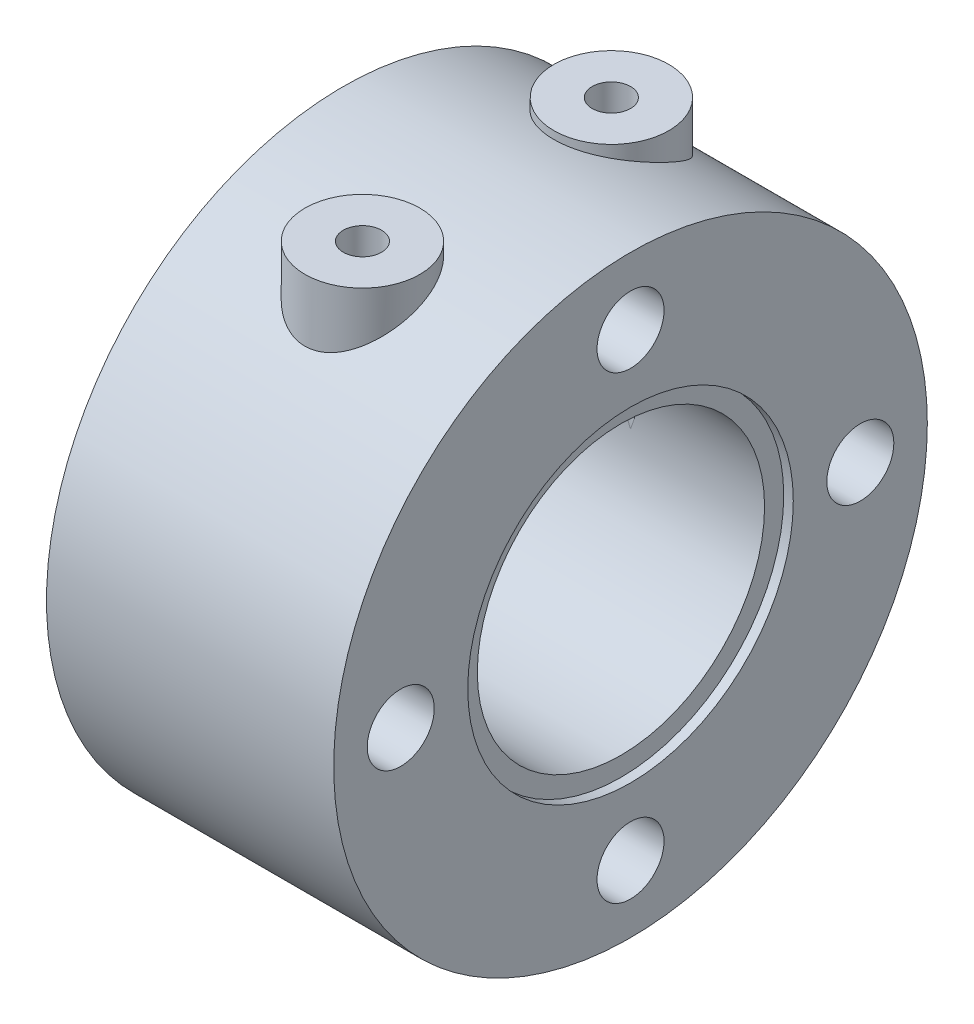
SolidWorks part; units mm, degrees
ref_plane "Front Plane" through (0, 0, 0) normal (0, 0, 1) x (1, 0, 0)
ref_plane "Top Plane" through (0, 0, 0) normal (0, 1, 0) x (1, 0, 0)
ref_plane "Right Plane" through (0, 0, 0) normal (1, 0, 0) x (0, 0, -1)
sketch "Sketch2" plane through (0, 0, 0) normal (1, 0, 0) x (0, 0, -1)
  circle A0 centre (0, 0) radius 15.5
  circle A1 centre (0, 12) radius 1.75
  circle A2 centre (12, 0) radius 1.75
  circle A3 centre (0, -12) radius 1.75
  circle A4 centre (-12, 0) radius 1.75
  circle A5 centre (0, 0) radius 7.5
  circle A6 centre (0, 0) radius 8.5 construction
  point P14 (0, 0)
  dimension "D1" = 31
  dimension "D3" = 3.5
  dimension "D5" = 15
  dimension "D6" = 17
  dimension "D4" = 12
  dimension "D2" = 4
extrude "Flange" add sketch "Sketch2" along normal blind 15
sketch "Sketch3" plane through (15, 0, 0) normal (1, 0, 0) x (0, 0, -1)
  circle A0 centre (0, 0) radius 8.5
  dimension "D1" = 17
extrude "O-Ring Seat" cut sketch "Sketch3" against normal blind 0.5
ref_plane "MidPlane Reference" through (7.5, 0, 0) normal (-1, 0, 0) x (0, 0, 1)
mirror "Mirror1" about plane through (7.5, 0, 0) normal (-1, 0, 0) of "O-Ring Seat"
sketch "Sketch5" plane through (0, 0, 0) normal (0, 1, 0) x (1, 0, 0)
  line L0 (7.5, 15.4) -> (7.5, -15.4) construction
  circle A0 centre (7.5, 6.5) radius 1
  dimension "D1" = 2
  dimension "D2" = 6.5
extrude "Outlet" cut sketch "Sketch5" along normal through all
ref_plane "Plane2" through (0, 15.5, 0) normal (0, 1, 0) x (1, 0, 0)
sketch "Sketch6" plane through (0, 15.5, 0) normal (0, 1, 0) x (1, 0, 0)
  circle A2 centre (7.5, 6.5) radius 1
  circle A3 centre (7.5, 6.5) radius 3
  dimension "D1" = 2
extrude "Boss-Extrude2" add sketch "Sketch6" against normal up to next
mirror "Inlet" about plane through (0, 0, 0) normal (0, 0, 1) of "Boss-Extrude2", "Outlet"
